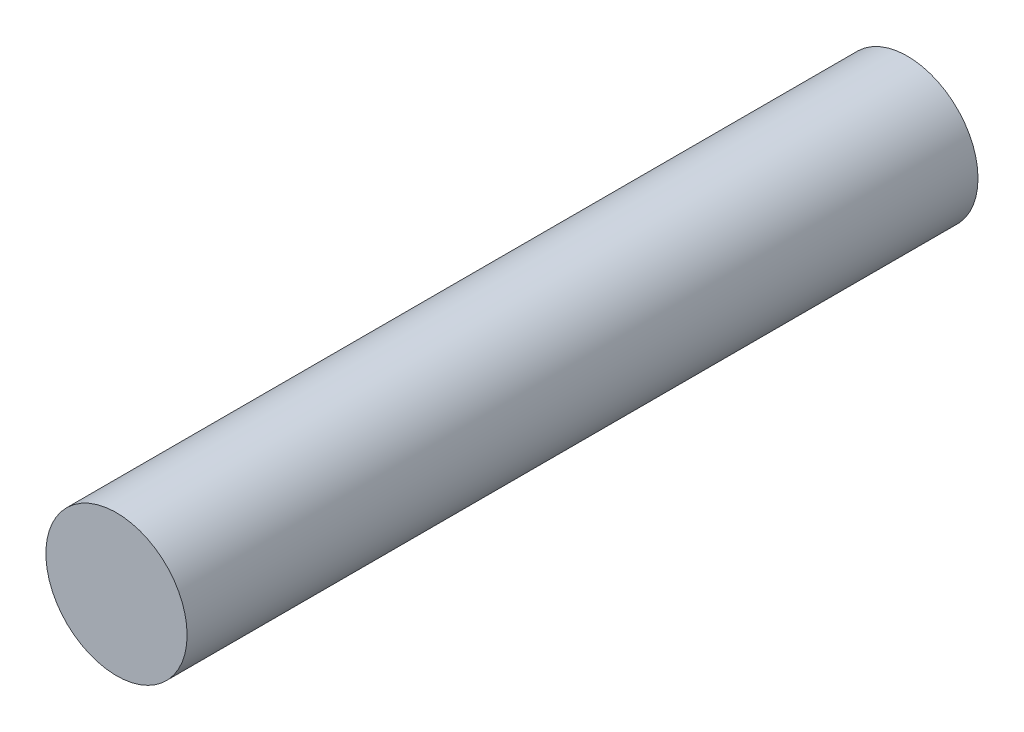
SolidWorks part; units mm, degrees
ref_plane "前视基准面" through (0, 0, 0) normal (0, 0, 1) x (1, 0, 0)
ref_plane "上视基准面" through (0, 0, 0) normal (0, 1, 0) x (1, 0, 0)
ref_plane "右视基准面" through (0, 0, 0) normal (1, 0, 0) x (0, 0, -1)
sketch "草图1" plane through (0, 0, 0) normal (0, 0, 1) x (1, 0, 0)
  circle A0 centre (0, 0) radius 2.5
  dimension "D1" = 5
extrude "凸台-拉伸1" add sketch "草图1" along normal blind 28
